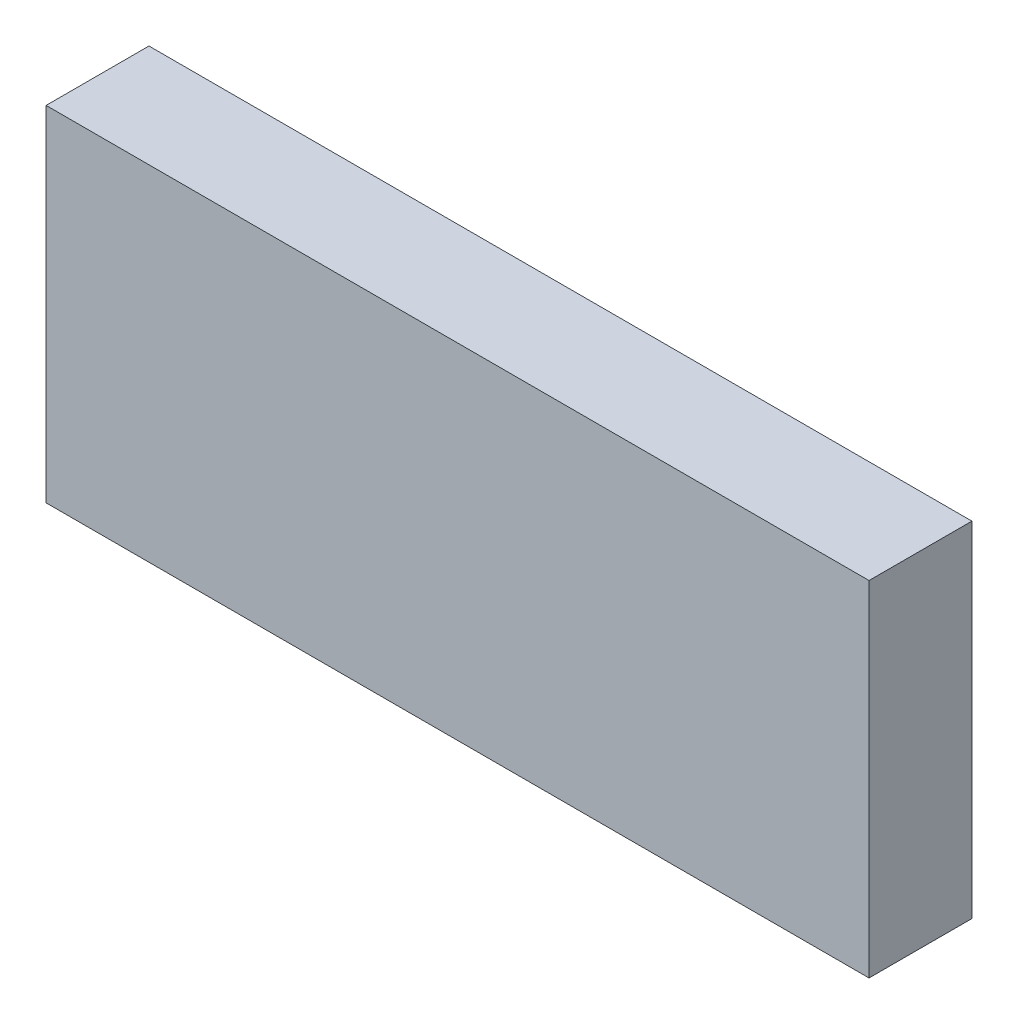
SolidWorks part; units mm, degrees
ref_plane "前视基准面" through (0, 0, 0) normal (0, 0, 1) x (1, 0, 0)
ref_plane "上视基准面" through (0, 0, 0) normal (0, 1, 0) x (1, 0, 0)
ref_plane "右视基准面" through (0, 0, 0) normal (1, 0, 0) x (0, 0, -1)
other "Configuration Table"
sketch "草图1" plane through (0, 0, 0) normal (0, 0, 1) x (1, 0, 0)
  line L1 (-5.9758, 5.95) -> (14.3442, 5.95)
  line L2 (-5.9758, 5.95) -> (-5.9758, -2.55)
  line L3 (-5.9758, -2.55) -> (14.3442, -2.55)
  line L4 (14.3442, 5.95) -> (14.3442, -2.55)
  dimension "D1" = 8.5
  dimension "D2" = 20.32
extrude "凸台-拉伸1" add sketch "草图1" along normal blind 2.54
